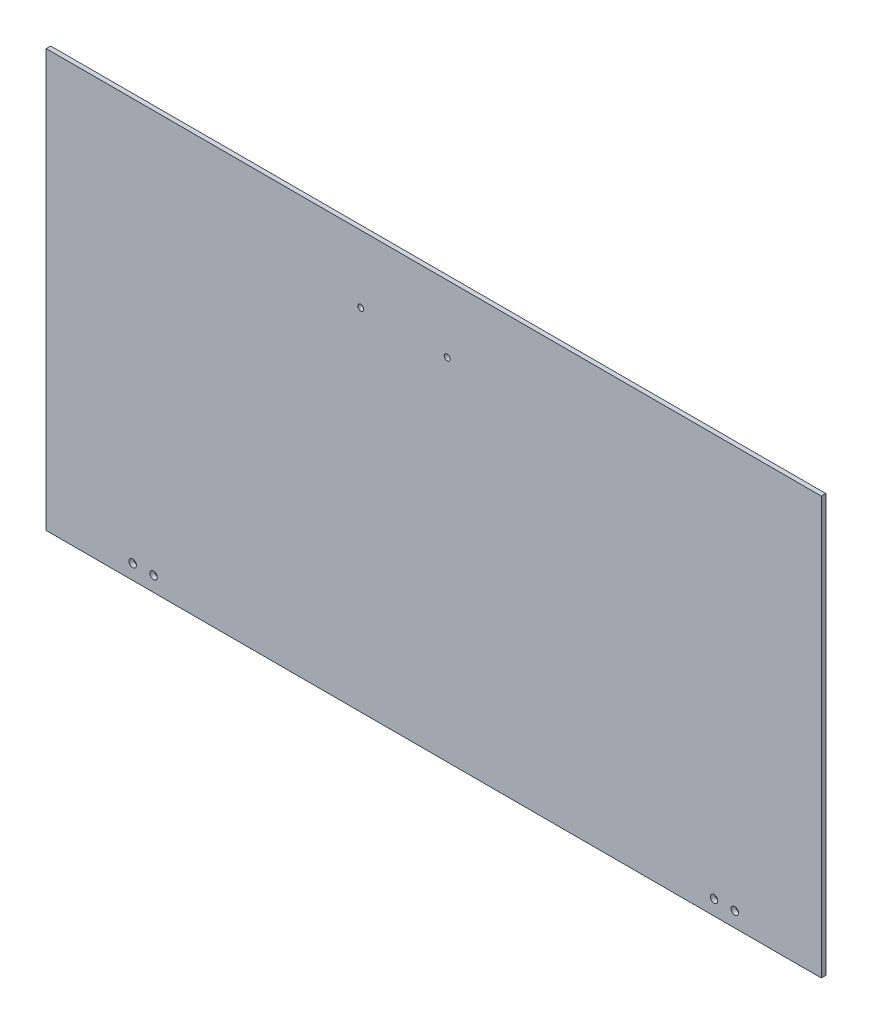
SolidWorks part; units mm, degrees
ref_plane "Płaszczyzna przednia" through (0, 0, 0) normal (0, 0, 1) x (1, 0, 0)
ref_plane "Płaszczyzna górna" through (0, 0, 0) normal (0, 1, 0) x (1, 0, 0)
ref_plane "Płaszczyzna prawa" through (0, 0, 0) normal (1, 0, 0) x (0, 0, -1)
sketch "Sketch1" plane through (0, 0, 0) normal (0, 0, 1) x (1, 0, 0)
  line L1 (0, 0) -> (520, 0)
  line L2 (0, 0) -> (0, 280)
  line L3 (0, 280) -> (520, 280)
  line L4 (520, 0) -> (520, 280)
  line L5 (0, 0) -> (520, 280) construction
  line L6 (0, 280) -> (520, 0) construction
  point P4 (260, 140)
  dimension "D1" = 280
  dimension "D2" = 520
extrude "Boss-Extrude1" add sketch "Sketch1" along normal blind 3
hole_wizard "Ø5.0mm Dowel Hole1" positions "Sketch2" profile "Sketch3" hole size "Ø5.0" standard "ANSI Metric" end condition up to next
sketch "Sketch2" plane through (0, 0, 3) normal (0, 0, 1) x (1, 0, 0)
  point P0 (462, 10)
  point P3 (448, 10)
  point P6 (72, 10)
  point P9 (58, 10)
sketch "Sketch3" plane through (462, 10, 3) normal (1, 0, 0) x (0, -1, 0)
  line L0 (0, 0) -> (0, 3)
  line L1 (0, 3) -> (2.5, 3)
  line L2 (2.5, 3) -> (2.5, 0)
  line L5 (2.5, 0) -> (0, 0)
  line L11 (0, -6.35) -> (0, 107.95) construction
  dimension "Thru Hole Dia." = 5
  dimension "Thru Hole Depth" = 3
hole_wizard "Ø4.0mm Dowel Hole1" positions "Sketch4" profile "Sketch5" hole size "Ø4.0" standard "ANSI Metric" end condition up to next
sketch "Sketch4" plane through (0, 0, 0) normal (0, 0, -1) x (-1, 0, 0)
  point P0 (-269, 235)
  point P3 (-211, 235)
sketch "Sketch5" plane through (269, 235, 0) normal (1, 0, 0) x (0, 1, 0)
  line L0 (0, 0) -> (0, 3)
  line L1 (0, 3) -> (2, 3)
  line L2 (2, 3) -> (2, 0)
  line L5 (2, 0) -> (0, 0)
  line L11 (0, -6.35) -> (0, 107.95) construction
  dimension "Thru Hole Dia." = 4
  dimension "Thru Hole Depth" = 3
